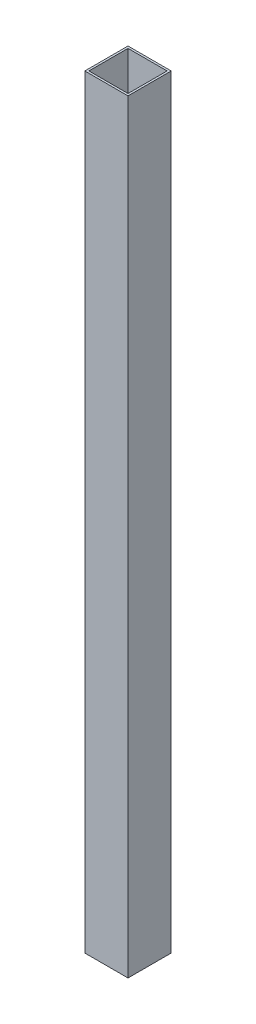
SolidWorks part; units mm, degrees
ref_plane "Front Plane" through (0, 0, 0) normal (0, 0, 1) x (1, 0, 0)
ref_plane "Top Plane" through (0, 0, 0) normal (0, 1, 0) x (1, 0, 0)
ref_plane "Right Plane" through (0, 0, 0) normal (1, 0, 0) x (0, 0, -1)
sketch "Sketch2" plane through (0, 0, 0) normal (0, 1, 0) x (1, 0, 0)
  line L0 (-11.5, 11.5) -> (11.5, 11.5)
  line L1 (-12.7, -12.7) -> (12.7, -12.7)
  line L2 (-12.7, -12.7) -> (-12.7, 12.7)
  line L3 (-12.7, 12.7) -> (12.7, 12.7)
  line L4 (12.7, -12.7) -> (12.7, 12.7)
  line L5 (-12.7, -12.7) -> (12.7, 12.7) construction
  line L6 (-12.7, 12.7) -> (12.7, -12.7) construction
  line L7 (11.5, -11.5) -> (11.5, 11.5)
  line L8 (-11.5, -11.5) -> (11.5, -11.5)
  line L9 (-11.5, -11.5) -> (-11.5, 11.5)
  point P0 (0, 0)
  dimension "D1" = 25.4
  dimension "D3" = 1.2
extrude "Boss-Extrude1" add sketch "Sketch2" along normal blind 449.2
